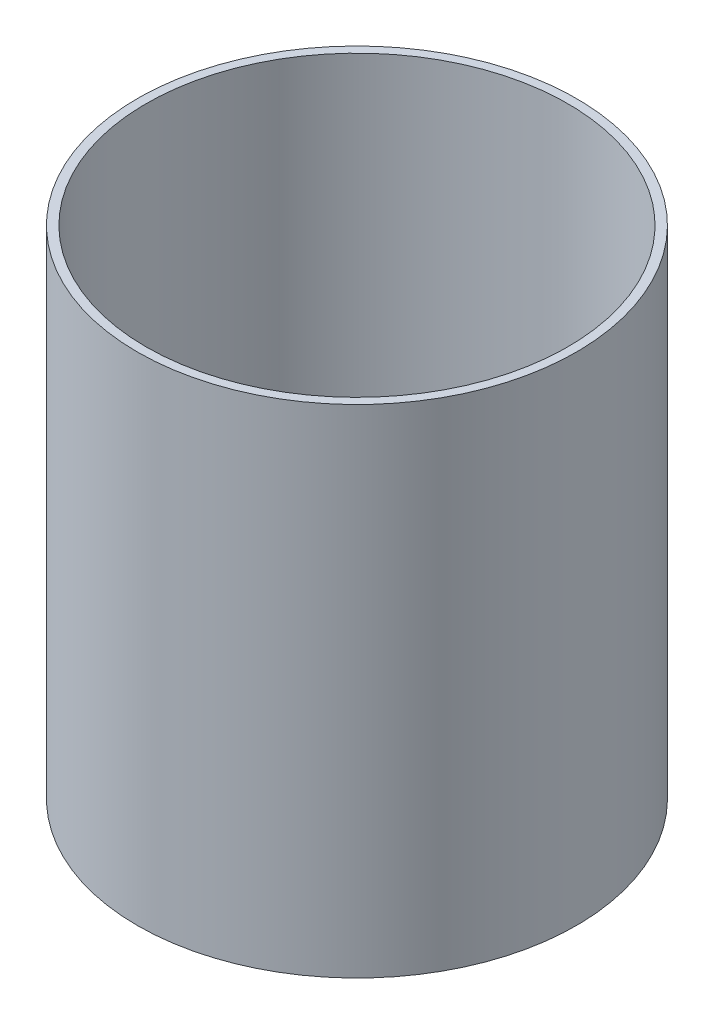
SolidWorks part; units mm, degrees
material "PTFE (general)"
ref_plane "Front Plane" through (0, 0, 0) normal (0, 0, 1) x (1, 0, 0)
ref_plane "Top Plane" through (0, 0, 0) normal (0, 1, 0) x (1, 0, 0)
ref_plane "Right Plane" through (0, 0, 0) normal (1, 0, 0) x (0, 0, -1)
sketch "Sketch1" plane through (0, 0, 0) normal (0, 1, 0) x (-0.9996, 0, 0.0287)
  circle A1 centre (-14.1407, -23.8948) radius 24.401
  circle A3 centre (-14.1407, -23.8948) radius 25.417
  dimension "D3" = 1.016
extrude "Boss-Extrude1" add sketch "Sketch1" along normal blind 57.5
